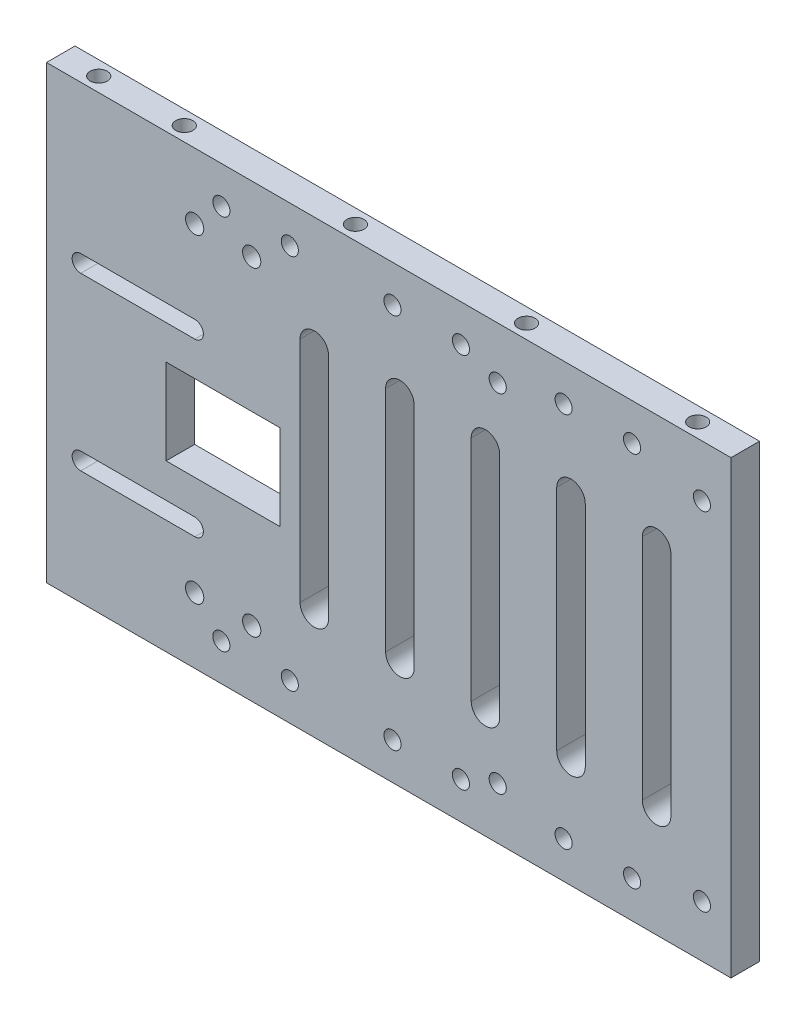
SolidWorks part; units mm, degrees
ref_plane "前视基准面" through (0, 0, 0) normal (0, 0, 1) x (1, 0, 0)
ref_plane "上视基准面" through (0, 0, 0) normal (0, 1, 0) x (1, 0, 0)
ref_plane "右视基准面" through (0, 0, 0) normal (1, 0, 0) x (0, 0, -1)
other "Configuration Table"
sketch "草图1" plane through (0, 0, 0) normal (0, 0, 1) x (1, 0, 0)
  line L1 (-60, -39.5) -> (60, -39.5)
  line L2 (-60, -39.5) -> (-60, 39.5)
  line L3 (-60, 39.5) -> (60, 39.5)
  line L4 (60, -39.5) -> (60, 39.5)
  line L5 (-60, -39.5) -> (60, 39.5) construction
  line L6 (-60, 39.5) -> (60, -39.5) construction
  point P0 (0, 0)
  dimension "D1" = 79
  dimension "D2" = 120
extrude "凸台-拉伸1" add sketch "草图1" along normal blind 5
sketch "草图2" plane through (0, 0, 0) normal (0, 0, -1) x (-1, 0, 0)
  circle A0 centre (-42.656, -33) radius 3.1
  circle A1 centre (-30.656, -33) radius 3.1
extrude "切除-拉伸1" cut sketch "草图2" against normal blind 2
sketch "草图3" plane through (0, 0, 2) normal (0, 0, -1) x (-1, 0, 0)
  circle A0 centre (-42.656, -33) radius 1.5
  circle A1 centre (-30.656, -33) radius 1.5
extrude "切除-拉伸2" cut sketch "草图3" against normal through all
pattern_linear "阵列(线性)1" count 3 spacing 30 along (-1, 0, 0) of "切除-拉伸1", "切除-拉伸2"
mirror "镜向2" about plane through (0, 0, 0) normal (0, 1, 0) of "阵列(线性)1", "切除-拉伸1", "切除-拉伸2"
sketch "草图4" plane through (0, 0, 0) normal (0, 0, -1) x (-1, 0, 0)
  line L0 (34, 12) -> (54, 12) construction
  line L1 (34, 15.1) -> (54, 15.1)
  line L2 (34, 8.9) -> (54, 8.9)
  line L3 (60, 39.5) -> (60, -39.5) construction
  line L4 (34.3421, -3) -> (54.815, -3) construction
  line L5 (34.3421, 17) -> (34.3421, -23) construction
  line L6 (54.815, 17) -> (54.815, -6) construction
  line L7 (34, -18) -> (54, -18) construction
  line L8 (34, -21.1) -> (54, -21.1)
  line L9 (34, -14.9) -> (54, -14.9)
  arc A4 (34, 15.1) -> (34, 8.9) centre (34, 12) ccw
  arc A5 (54, 8.9) -> (54, 15.1) centre (54, 12) ccw
  arc A6 (34, -21.1) -> (34, -14.9) centre (34, -18) cw
  arc A7 (54, -14.9) -> (54, -21.1) centre (54, -18) cw
  point P8 (44, 12)
  point P17 (44, -18)
  dimension "D1" = 20
  dimension "D2" = 6
extrude "切除-拉伸3" cut sketch "草图4" against normal blind 1.5
sketch "草图5" plane through (0, 0, 1.5) normal (0, 0, -1) x (-1, 0, 0)
  line L0 (54, 12) -> (34, 12) construction
  line L1 (54, 10.5) -> (34, 10.5)
  line L2 (54, 13.5) -> (34, 13.5)
  line L3 (60, 39.5) -> (60, -39.5) construction
  line L4 (34.3421, -3) -> (54.815, -3) construction
  line L5 (54.815, 17) -> (54.815, -6) construction
  line L6 (54, -18) -> (34, -18) construction
  line L7 (54, -16.5) -> (34, -16.5)
  line L8 (54, -19.5) -> (34, -19.5)
  arc A0 (54, 10.5) -> (54, 13.5) centre (54, 12) ccw
  arc A1 (34, 13.5) -> (34, 10.5) centre (34, 12) ccw
  arc A2 (54, -16.5) -> (54, -19.5) centre (54, -18) cw
  arc A3 (34, -19.5) -> (34, -16.5) centre (34, -18) cw
  point P4 (44, 12)
  point P18 (44, -18)
  dimension "D1" = 20
  dimension "D2" = 6
extrude "切除-拉伸4" cut sketch "草图5" against normal through all
sketch "草图7" plane through (0, -39.5, 0) normal (0, -1, 0) x (1, 0, 0)
  line L0 (46.656, 31) -> (46.656, 5) construction
  circle A0 centre (51.656, 2.5) radius 1.5
  circle A1 centre (21.656, 2.5) radius 1.5
  circle A2 centre (-8.344, 2.5) radius 1.5
  circle A3 centre (-38.344, 2.5) radius 1.5
  circle A4 centre (-53.344, 2.5) radius 1.5
  dimension "D1" = 5
  dimension "D2" = 15
extrude "切除-拉伸6" cut sketch "草图7" against normal blind 5
mirror "镜向3" about plane through (0, 0, 0) normal (0, 1, 0) of "切除-拉伸6"
sketch "草图9" plane through (0, 0, 0) normal (0, 0, -1) x (-1, 0, 0)
  line L0 (-46.9526, -20.2662) -> (-46.9526, 19.7338) construction
  line L1 (-49.4526, -20.2662) -> (-49.4526, 19.7338)
  line L2 (-44.4526, -20.2662) -> (-44.4526, 19.7338)
  line L3 (-31.9526, -20.2662) -> (-31.9526, 19.7338) construction
  line L4 (-34.4526, -20.2662) -> (-34.4526, 19.7338)
  line L5 (-29.4526, -20.2662) -> (-29.4526, 19.7338)
  line L6 (-16.9526, -20.2662) -> (-16.9526, 19.7338) construction
  line L7 (-19.4526, -20.2662) -> (-19.4526, 19.7338)
  line L8 (-14.4526, -20.2662) -> (-14.4526, 19.7338)
  line L9 (-1.9526, -20.2662) -> (-1.9526, 19.7338) construction
  line L10 (-4.4526, -20.2662) -> (-4.4526, 19.7338)
  line L11 (0.5474, -20.2662) -> (0.5474, 19.7338)
  line L12 (13.0474, -20.2662) -> (13.0474, 19.7338) construction
  line L13 (10.5474, -20.2662) -> (10.5474, 19.7338)
  line L14 (15.5474, -20.2662) -> (15.5474, 19.7338)
  circle A0 centre (24.0277, -28) radius 1.6 construction
  circle A1 centre (34.0277, -28) radius 1.6 construction
  circle A2 centre (24.0277, 28) radius 1.6 construction
  circle A3 centre (34.0277, 28) radius 1.6 construction
  circle A4 centre (24.0277, -28) radius 1.6
  circle A5 centre (34.0277, -28) radius 1.6
  circle A6 centre (24.0277, 28) radius 1.6
  circle A7 centre (34.0277, 28) radius 1.6
  arc A8 (-49.4526, -20.2662) -> (-44.4526, -20.2662) centre (-46.9526, -20.2662) ccw
  arc A9 (-44.4526, 19.7338) -> (-49.4526, 19.7338) centre (-46.9526, 19.7338) ccw
  arc A10 (-34.4526, -20.2662) -> (-29.4526, -20.2662) centre (-31.9526, -20.2662) ccw
  arc A11 (-29.4526, 19.7338) -> (-34.4526, 19.7338) centre (-31.9526, 19.7338) ccw
  circle A16 centre (-19.1038, 30.4) radius 1.5
  circle A17 centre (-54.9038, 30.4) radius 1.5
  circle A18 centre (-19.1038, -30.4) radius 1.5
  circle A19 centre (-54.9038, -30.4) radius 1.5
  arc A20 (-19.4526, -20.2662) -> (-14.4526, -20.2662) centre (-16.9526, -20.2662) ccw
  arc A21 (-14.4526, 19.7338) -> (-19.4526, 19.7338) centre (-16.9526, 19.7338) ccw
  arc A22 (-4.4526, -20.2662) -> (0.5474, -20.2662) centre (-1.9526, -20.2662) ccw
  arc A23 (0.5474, 19.7338) -> (-4.4526, 19.7338) centre (-1.9526, 19.7338) ccw
  arc A24 (10.5474, -20.2662) -> (15.5474, -20.2662) centre (13.0474, -20.2662) ccw
  arc A25 (15.5474, 19.7338) -> (10.5474, 19.7338) centre (13.0474, 19.7338) ccw
  point P17 (-46.9526, -0.2662)
  point P31 (-31.9526, -0.2662)
  point P38 (-16.9526, -0.2662)
  point P45 (-1.9526, -0.2662)
  point P52 (13.0474, -0.2662)
  dimension "D1" = 5
extrude "切除-拉伸7" cut sketch "草图9" against normal through all
sketch "草图11" plane through (0, 0, 5) normal (0, 0, 1) x (1, 0, 0)
  line L0 (-29.0277, 4.5) -> (-29.0277, -10.5)
  line L4 (-39.0277, -10.5) -> (-19.0277, -10.5)
  line L5 (-19.0277, -10.5) -> (-19.0277, 4.5)
  line L6 (-19.0277, 4.5) -> (-39.0277, 4.5)
  line L7 (-39.0277, 4.5) -> (-39.0277, -10.5)
  line L8 (-39.0277, -10.5) -> (-19.0277, -10.5)
  line L9 (-19.0277, -10.5) -> (-19.0277, 4.5)
  line L10 (-19.0277, 4.5) -> (-39.0277, 4.5)
  line L11 (-39.0277, 4.5) -> (-39.0277, -10.5)
  dimension "D1" = 0
extrude "切除-拉伸8" cut sketch "草图11" against normal through all contours L9 L10 L0 L8 | L10 L11 L8 L0
